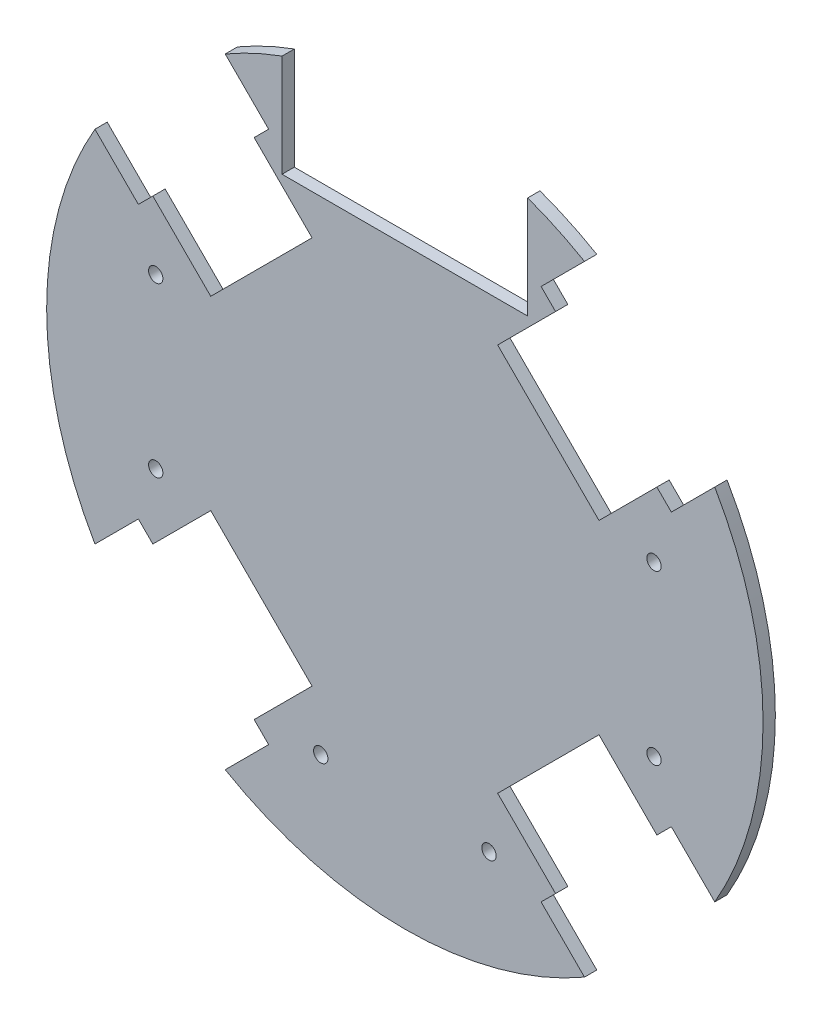
SolidWorks part; units mm, degrees
ref_plane "Front Plane" through (0, 0, 0) normal (0, 0, 1) x (1, 0, 0)
ref_plane "Top Plane" through (0, 0, 0) normal (0, 1, 0) x (1, 0, 0)
ref_plane "Right Plane" through (0, 0, 0) normal (1, 0, 0) x (0, 0, -1)
sketch "Sketch1" plane through (0, 0, 0) normal (0, 0, 1) x (1, 0, 0)
  line L0 (-30, 57.1964) -> (30, 57.1964)
  line L1 (30, 57.1964) -> (30, 82.1964)
  line L2 (30, 82.1964) -> (-30, 82.1964) construction
  line L3 (-30, 82.1964) -> (-30, 57.1964)
  arc A1 (-30, 82.1964) -> (30, 82.1964) centre (0, 0) ccw
  point P2 (0, 0)
  point P6 (96.6987, -57.1964)
  point P7 (0, 0)
  dimension "D1" = 87.5
  dimension "D2" = 60
  dimension "D3" = 25
extrude "Boss-Extrude1" add sketch "Sketch1" against normal blind 3
sketch "Sketch3" plane through (0, 0, 0) normal (0, 0, 1) x (1, 0, 0)
  line L0 (-87.5, 0) -> (0, 0) construction
  line L1 (0, 0) -> (-35.0426, 35.0426) construction
  line L2 (-47.4169, 22.6682) -> (-22.6682, 47.4169)
  line L3 (-47.4169, 22.6682) -> (-61.5591, 36.8103)
  line L4 (-61.5591, 36.8103) -> (-65.0946, 33.2748)
  line L5 (-65.0946, 33.2748) -> (-75.7012, 43.8814)
  line L6 (-75.7012, 43.8814) -> (-43.8814, 75.7012) construction
  line L7 (-43.8814, 75.7012) -> (-33.2748, 65.0946)
  line L8 (-33.2748, 65.0946) -> (-36.8103, 61.5591)
  line L9 (-36.8103, 61.5591) -> (-22.6682, 47.4169)
  line L10 (-61.5591, 36.8103) -> (-36.8103, 61.5591) construction
  line L11 (-35.0426, 35.0426) -> (-49.1847, 49.1847) construction
  line L12 (-49.1847, 49.1847) -> (-59.7913, 59.7913) construction
  line L13 (-60.852, 20.5469) -> (-20.5469, 60.852) construction
  arc A0 (-30, 82.1964) -> (30, 82.1964) centre (0, 0) ccw construction
  arc A1 (-43.8814, 75.7012) -> (-75.7012, 43.8814) centre (0, 0) ccw
  arc A2 (-87.5, 0) -> (30, 82.1964) centre (0, 0) ccw
  circle A3 centre (-60.852, 20.5469) radius 1.75
  circle A4 centre (-20.5469, 60.852) radius 1.75
  point P19 (-40.6994, 40.6994)
  arc M14 (-30, 82.1964) -> (30, 82.1964) centre (0, 0) ccw
  dimension "D8" = 3.5
  dimension "D1" = 45
  dimension "D2" = 35
  dimension "D3" = 45
  dimension "D4" = 15
  dimension "D5" = 20
  dimension "D6" = 57
  dimension "D7" = 8
extrude "Cut-Extrude1" cut sketch "Sketch3" against normal through all contours L9 L8 L7 L5 L4 L3 L2 M14 | A3 | A4
mirror "Mirror1" about plane through (0, 0, 0) normal (1, 0, 0) of "Cut-Extrude1" second plane through (0, 0, 0) second plane normal (0, 1, 0)
